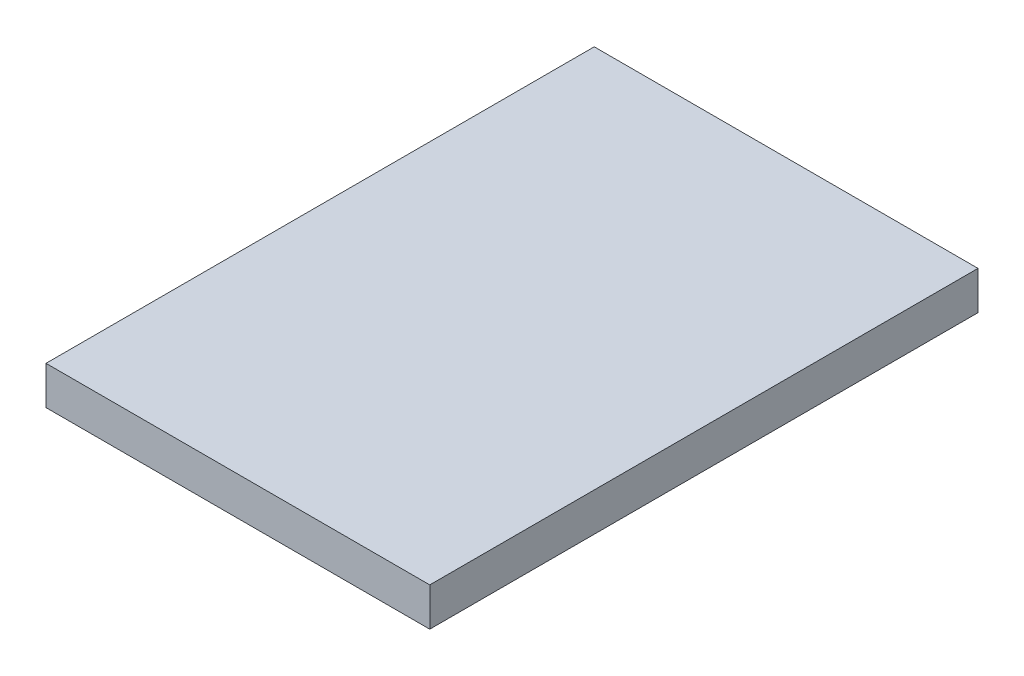
SolidWorks part; units mm, degrees
ref_plane "Front Plane" through (0, 0, 0) normal (0, 0, 1) x (1, 0, 0)
ref_plane "Top Plane" through (0, 0, 0) normal (0, 1, 0) x (1, 0, 0)
ref_plane "Right Plane" through (0, 0, 0) normal (1, 0, 0) x (0, 0, -1)
sketch "Sketch1" plane through (0, 0, 0) normal (0, 1, 0) x (1, 0, 0)
  line L1 (-35, -50) -> (35, -50)
  line L2 (-35, -50) -> (-35, 50)
  line L3 (-35, 50) -> (35, 50)
  line L4 (35, -50) -> (35, 50)
  line L5 (-35, -50) -> (35, 50) construction
  line L6 (-35, 50) -> (35, -50) construction
  point P0 (0, 0)
  dimension "D1" = 70
  dimension "D2" = 100
extrude "Boss-Extrude1" add sketch "Sketch1" along normal blind 7
